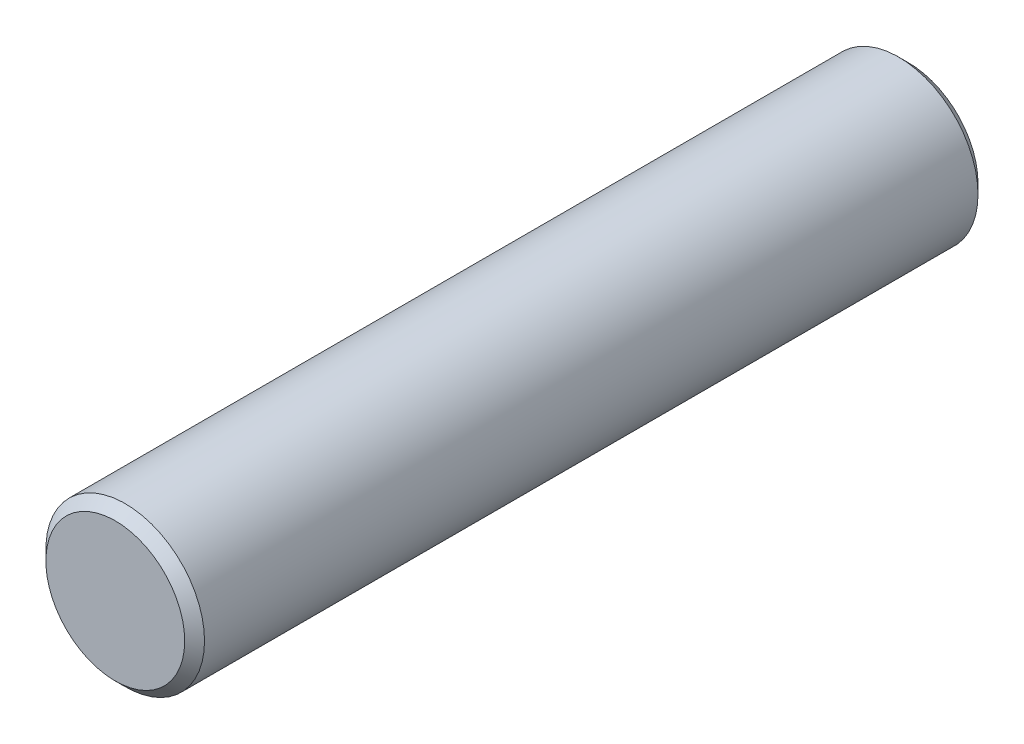
SolidWorks part; units mm, degrees
ref_plane "Front Plane" through (0, 0, 0) normal (0, 0, 1) x (1, 0, 0)
ref_plane "Top Plane" through (0, 0, 0) normal (0, 1, 0) x (1, 0, 0)
ref_plane "Right Plane" through (0, 0, 0) normal (1, 0, 0) x (0, 0, -1)
sketch "Sketch1" plane through (0, 0, 0) normal (0, 0, 1) x (1, 0, 0)
  circle A0 centre (0, 0) radius 2
  dimension "D1" = 4
extrude "Boss-Extrude1" add sketch "Sketch1" along normal blind 20
chamfer "Chamfer1" distance 0.25 angle 45 2 edges at (2, 0, 0) (2, 0, 20)
